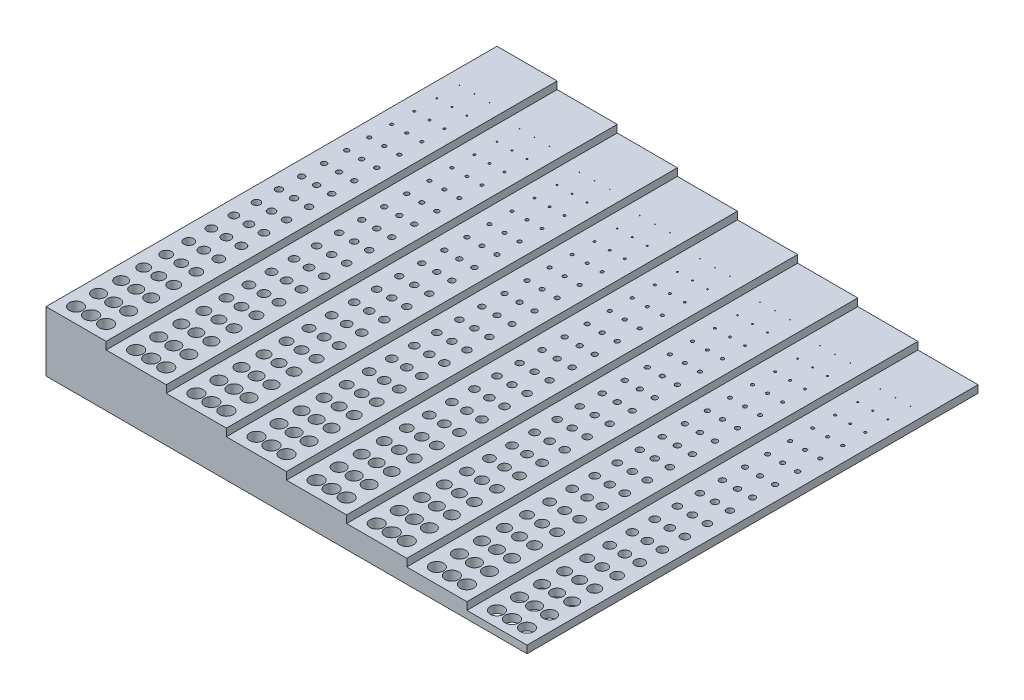
SolidWorks part; units mm, degrees
ref_plane "Front Plane" through (0, 0, 0) normal (0, 0, 1) x (1, 0, 0)
ref_plane "Top Plane" through (0, 0, 0) normal (0, 1, 0) x (1, 0, 0)
ref_plane "Right Plane" through (0, 0, 0) normal (1, 0, 0) x (0, 0, -1)
sketch "Sketch3" plane through (0, 0, 0) normal (0, 0, 1) x (1, 0, 0)
  line L0 (0, 0) -> (0, 4)
  line L1 (0, -55) -> (0, 55) construction
  line L2 (0, 4) -> (4, 4)
  line L3 (4, 4) -> (4, 3.5)
  line L4 (4, 3.5) -> (8, 3.5)
  line L5 (8, 3.5) -> (8, 3)
  line L6 (8, 3) -> (12, 3)
  line L7 (12, 3) -> (12, 2.5)
  line L8 (12, 2.5) -> (16, 2.5)
  line L9 (16, 2.5) -> (16, 2)
  line L10 (16, 2) -> (20, 2)
  line L12 (55, 0) -> (-55, 0) construction
  line L13 (32, 0) -> (0, 0)
  line L14 (20, 2) -> (20, 1.5)
  line L15 (20, 1.5) -> (24, 1.5)
  line L16 (24, 1.5) -> (24, 1)
  line L17 (24, 1) -> (28, 1)
  line L18 (28, 1) -> (28, 0.5)
  line L19 (28, 0.5) -> (32, 0.5)
  line L20 (32, 0.5) -> (32, 0)
  point P15 (31.3934, 0.5169)
  point P18 (26.5636, 0)
  dimension "D1" = 4
  dimension "D2" = 4
  dimension "D3" = 0.5
extrude "Boss-Extrude1" add sketch "Sketch3" along normal blind 30
sketch "Sketch4" plane through (0, 4, 0) normal (0, 1, 0) x (1, 0, 0)
  line L0 (0, -29) -> (32, -29) construction
  line L1 (0, -2.2) -> (0, 2.2) construction
  line L2 (32, -30) -> (32, 0) construction
  line L3 (4, -30) -> (0, -30) construction
  line L4 (1, -29) -> (1, 0) construction
  line L5 (-2.2, 0) -> (2.2, 0) construction
  circle A0 centre (1, -29) radius 0.45
  circle A14 centre (1, -27.5) radius 0.425
  circle A15 centre (1, -26) radius 0.4
  circle A16 centre (1, -24.5) radius 0.375
  circle A17 centre (1, -23) radius 0.35
  circle A18 centre (1, -21.5) radius 0.325
  circle A19 centre (1, -20) radius 0.3
  circle A20 centre (1, -18.5) radius 0.275
  circle A21 centre (1, -17) radius 0.25
  circle A22 centre (1, -15.5) radius 0.225
  circle A23 centre (1, -14) radius 0.2
  circle A24 centre (1, -12.5) radius 0.175
  circle A25 centre (1, -11) radius 0.15
  circle A26 centre (1, -9.5) radius 0.125
  circle A27 centre (1, -8) radius 0.1
  circle A28 centre (1, -6.5) radius 0.075
  circle A29 centre (1, -5) radius 0.05
  circle A30 centre (1, -3.5) radius 0.025
  dimension "D3" = 0.9
  dimension "D5" = 0.8
  dimension "D4" = 0.85
  dimension "D6" = 0.75
  dimension "D7" = 0.7
  dimension "D8" = 0.65
  dimension "D9" = 0.6
  dimension "D10" = 0.55
  dimension "D11" = 0.5
  dimension "D12" = 0.45
  dimension "D13" = 0.4
  dimension "D14" = 0.35
  dimension "D15" = 0.3
  dimension "D16" = 0.25
  dimension "D17" = 0.2
  dimension "D18" = 0.15
  dimension "D19" = 0.1
  dimension "D20" = 0.05
  dimension "D1" = 1
  dimension "D2" = 1
extrude "Cut-Extrude1" cut sketch "Sketch4" against normal up to next
pattern_linear "LPattern1" count 31 spacing 1 along (1, 0, 0) skipping (3, 0), (7, 0), (11, 0), (15, 0), (19, 0), (23, 0), (27, 0) of "Cut-Extrude1"
